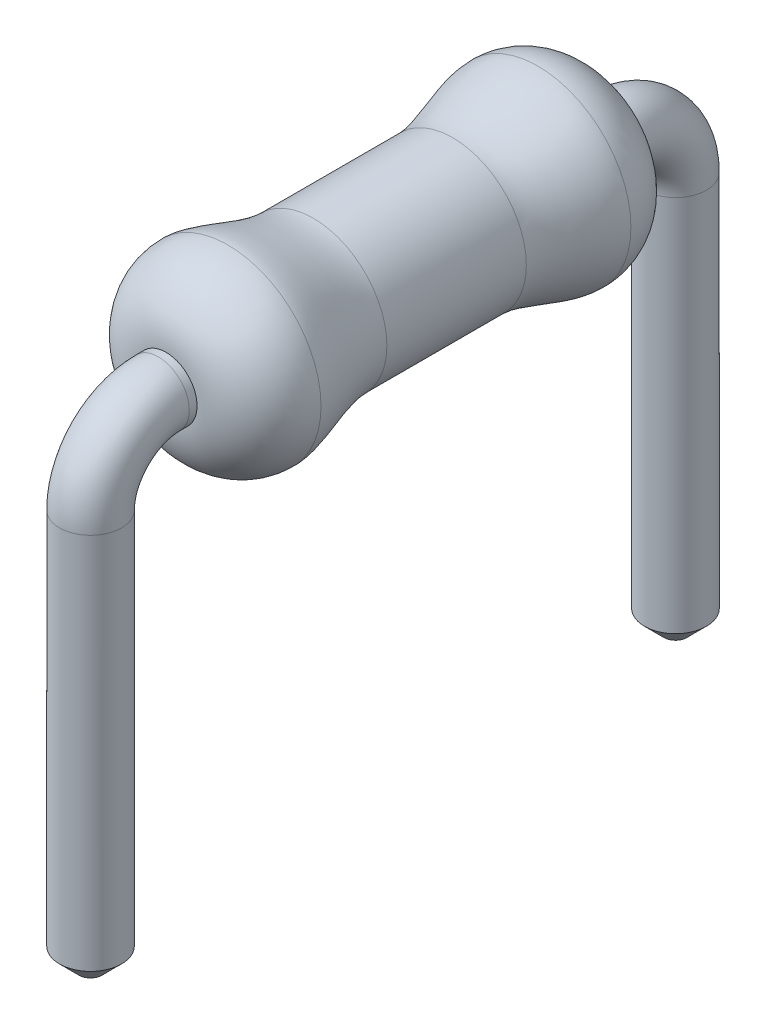
SolidWorks part; units mm, degrees
ref_plane "Front Plane" through (0, 0, 0) normal (0, 0, 1) x (1, 0, 0)
ref_plane "Top Plane" through (0, 0, 0) normal (0, 1, 0) x (1, 0, 0)
ref_plane "Right Plane" through (0, 0, 0) normal (1, 0, 0) x (0, 0, -1)
sketch "Sketch1" plane through (0, 0, 0) normal (1, 0, 0) x (0, 0, -1)
  line L0 (-2.9, 3) -> (2.9, 3)
  line L1 (-3.775, 2.125) -> (-3.775, -3)
  line L2 (3.775, 2.125) -> (3.775, -3)
  arc A0 (-3.775, 2.125) -> (-2.9, 3) centre (-2.9, 2.125) cw
  arc A1 (2.9, 3) -> (3.775, 2.125) centre (2.9, 2.125) cw
  point P7 (0, 3)
  point P10 (0, 0)
  point P11 (0, 0)
  point P12 (0, 0)
  dimension "D3" = 5.8
  dimension "D1" = 3
  dimension "D2" = 3
  dimension "D4" = 7.55
ref_plane "Plane1" through (0, -3, 3.775) normal (0, -1, 0) x (-1, 0, 0)
sketch "Sketch2" plane through (0, -3, 3.775) normal (0, -1, 0) x (-1, 0, 0)
  line L0 (0, 0.875) -> (0, 0) construction
  circle A0 centre (0, 0) radius 0.4
  point P4 (0, -0.5423)
  dimension "D1" = 0.8
sweep "Sweep1" add profiles "Sketch2" path "Sketch1"
chamfer "Chamfer1" distance 0.25 angle 45 2 edges at (0, -3, 3.375) (0, -3, -3.375)
sketch "Sketch4" plane through (0, 0, 0) normal (1, 0, 0) x (0, 0, -1)
  line L0 (2.9, 3.4) -> (-2.9, 3.4) construction
  line L1 (2.8, 3.4) -> (-2.8, 3.4)
  line L2 (-2.9, 3) -> (2.9, 3) construction
  line L3 (-5.5081, 3) -> (5.2987, 3) construction
  line L4 (-0.9, 3.95) -> (0.9, 3.95)
  line L5 (-2.8, 3.4) -> (-2.8, 1.7739) construction
  line L6 (2.8, 3.4) -> (2.8, 1.7739) construction
  line L7 (1.3088, 3.95) -> (0.9235, 3.95) construction
  line L8 (1.9924, 4.2) -> (1.5326, 4.2) construction
  line L9 (-0.554, 3.95) -> (-1.1515, 3.95) construction
  line L10 (-1.6501, 4.2) -> (-2.1003, 4.2) construction
  line L11 (0, 3.95) -> (0, 0) construction
  arc A0 (-2.8, 3.4) -> (-2, 4.2) centre (-2, 3.4) cw
  arc A1 (2.8, 3.4) -> (2, 4.2) centre (2, 3.4) ccw
  spline S0 degree 3 poles (-2, 4.2) (-1.7386, 4.2) (-1.2799, 3.95) (-0.9, 3.95) knots 0 0 0 0 1 1 1 1
  spline S1 degree 3 poles (0.9, 3.95) (1.2298, 3.95) (1.6775, 4.2) (2, 4.2) knots 0 0 0 0 1 1 1 1
  point P12 (0, 3.4)
  point P26 (-1.78, 4.2664)
  point P29 (1.9157, 4.1955)
  dimension "D2" = 0.8
  dimension "D1" = 5.6
  dimension "D3" = 1.8
  dimension "D4" = 1.9
  dimension "D5" = 4
revolve "Revolve1" add sketch "Sketch4" angle 360 about L3
